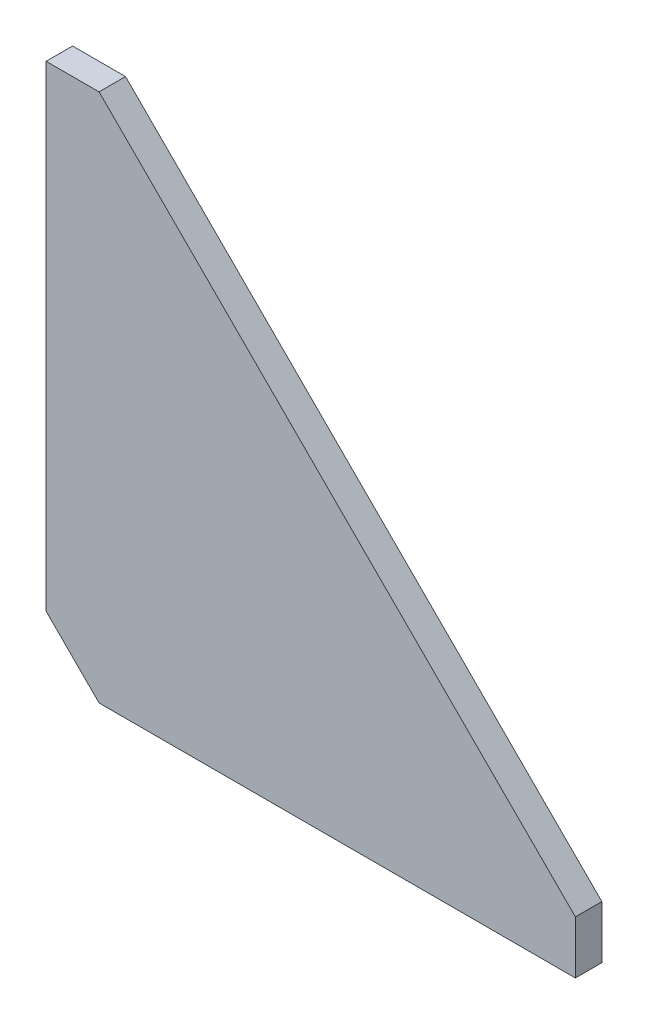
SolidWorks part; units mm, degrees
material "Сталь 3 ГОСТ 535-88"
ref_plane "Спереди" through (0, 0, 0) normal (0, 0, 1) x (1, 0, 0)
ref_plane "Сверху" through (0, 0, 0) normal (0, 1, 0) x (1, 0, 0)
ref_plane "Справа" through (0, 0, 0) normal (1, 0, 0) x (0, 0, -1)
sketch "Эскиз1" plane through (0, 0, 0) normal (0, 0, 1) x (1, 0, 0)
  line L0 (0, 0) -> (0, 100)
  line L1 (0, 100) -> (10, 100)
  line L2 (10, 100) -> (100, 10)
  line L3 (100, 10) -> (100, 0)
  line L4 (100, 0) -> (0, 0)
  dimension "D1" = 100
  dimension "D2" = 10
extrude "Бобышка-Вытянуть1" add sketch "Эскиз1" along normal mid plane 5
chamfer "Фаска1" distance 10 angle 45 1 edges at (0, 0, 0)
